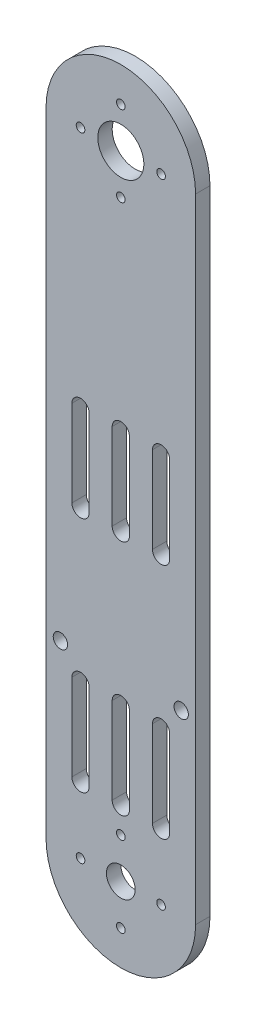
SolidWorks part; units mm, degrees
material "6061 合金"
ref_plane "前视基准面" through (0, 0, 0) normal (0, 0, 1) x (1, 0, 0)
ref_plane "上视基准面" through (0, 0, 0) normal (0, 1, 0) x (1, 0, 0)
ref_plane "右视基准面" through (0, 0, 0) normal (1, 0, 0) x (0, 0, -1)
other "质心 (COM)"
sketch "草图1" plane through (0, 0, 0) normal (0, 0, 1) x (1, 0, 0)
  line L0 (0, 23) -> (0, 53) construction
  line L4 (0, 23) -> (0, 53) construction
  line L23 (-3, 23) -> (-3, 53)
  line L87 (3, 23) -> (3, 53)
  line L88 (0, 23) -> (-14, 23) construction
  line L95 (-14, 23) -> (-14, 53) construction
  line L174 (-17, 23) -> (-17, 53)
  line L175 (-11, 23) -> (-11, 53)
  line L176 (0, 0) -> (0, 110) construction
  line L177 (-26, 220) -> (-26, 0)
  line L178 (-58.7183, 110) -> (53.7841, 110) construction
  line L179 (26, 220) -> (26, 0)
  line L180 (0, 220) -> (0, 161.5) construction
  line L181 (21, 62) -> (21, 110) construction
  line L182 (-21, 62) -> (-21, 110) construction
  line L183 (-19, 110) -> (-19, 131) construction
  line L184 (-31.1577, 62) -> (32.7845, 62) construction
  line L185 (2.4, 40.8) -> (18.4, 52.8) construction
  line L186 (20, 40) -> (20, 52) construction
  line L187 (3, 39) -> (19, 39) construction
  line L188 (3, 36) -> (19, 36) construction
  line L189 (2.4, 34.2) -> (18.4, 22.2) construction
  line L190 (20, 35) -> (20, 23) construction
  line L191 (-2.4, 34.2) -> (-18.4, 22.2) construction
  line L192 (-20, 35) -> (-20, 23) construction
  line L193 (-3, 36) -> (-19, 36) construction
  line L194 (-2.4, 40.8) -> (-18.4, 52.8) construction
  line L195 (-20, 40) -> (-20, 52) construction
  line L196 (-3, 39) -> (-19, 39) construction
  line L197 (20, 136) -> (20, 148) construction
  line L198 (2.4, 136.8) -> (18.4, 148.8) construction
  line L199 (-20, 136) -> (-20, 148) construction
  line L200 (20, 131) -> (20, 119) construction
  line L201 (-2.4, 136.8) -> (-18.4, 148.8) construction
  line L202 (3, 132) -> (19, 132) construction
  line L203 (2.4, 130.2) -> (18.4, 118.2) construction
  line L204 (-3, 135) -> (-19, 135) construction
  line L205 (-3, 132) -> (-19, 132) construction
  line L206 (-20, 131) -> (-20, 119) construction
  line L207 (-2.4, 130.2) -> (-18.4, 118.2) construction
  line L208 (3, 135) -> (19, 135) construction
  line L209 (14, 23) -> (14, 53) construction
  line L212 (17, 23) -> (17, 53)
  line L215 (0, 105.5) -> (0, 135.5) construction
  line L218 (-3, 105.5) -> (-3, 135.5)
  line L221 (11, 23) -> (11, 53)
  line L222 (0, 105.5) -> (0, 135.5) construction
  line L224 (3, 105.5) -> (3, 135.5)
  line L225 (0, 105.5) -> (-14, 105.5) construction
  line L226 (-14, 105.5) -> (-14, 135.5) construction
  line L227 (-17, 105.5) -> (-17, 135.5)
  line L228 (-11, 105.5) -> (-11, 135.5)
  line L229 (14, 105.5) -> (14, 135.5) construction
  line L230 (17, 105.5) -> (17, 135.5)
  line L231 (11, 105.5) -> (11, 135.5)
  arc A11 (-3, 23) -> (3, 23) centre (0, 23) ccw
  arc A187 (-26, 0) -> (26, 0) centre (0, 0) ccw
  circle A188 centre (0, 0) radius 5
  circle A189 centre (0, 0) radius 14 construction
  circle A190 centre (0, -14) radius 1.5
  circle A191 centre (0, 220) radius 22 construction
  circle A192 centre (0, 242) radius 2 construction
  circle A193 centre (0, 220) radius 8
  arc A194 (-26, 220) -> (26, 220) centre (0, 220) cw
  circle A195 centre (-14, 0) radius 1.5
  circle A196 centre (0, 14) radius 1.5
  circle A197 centre (14, 0) radius 1.5
  circle A198 centre (22, 220) radius 2 construction
  circle A199 centre (0, 198) radius 2 construction
  circle A200 centre (-22, 220) radius 2 construction
  circle A201 centre (-21, 62) radius 2.5
  circle A202 centre (21, 62) radius 2.5
  arc A203 (2.4, 40.8) -> (3, 39) centre (3, 40) ccw construction
  arc A204 (20, 52) -> (18.4, 52.8) centre (19, 52) ccw construction
  arc A205 (19, 39) -> (20, 40) centre (19, 40) ccw construction
  arc A206 (2.4, 34.2) -> (3, 36) centre (3, 35) cw construction
  arc A207 (20, 23) -> (18.4, 22.2) centre (19, 23) cw construction
  arc A208 (19, 36) -> (20, 35) centre (19, 35) cw construction
  arc A209 (-2.4, 34.2) -> (-3, 36) centre (-3, 35) ccw construction
  arc A210 (-20, 23) -> (-18.4, 22.2) centre (-19, 23) ccw construction
  arc A211 (-19, 36) -> (-20, 35) centre (-19, 35) ccw construction
  arc A212 (-20, 52) -> (-18.4, 52.8) centre (-19, 52) cw construction
  arc A213 (-19, 39) -> (-20, 40) centre (-19, 40) cw construction
  arc A214 (-2.4, 40.8) -> (-3, 39) centre (-3, 40) cw construction
  circle A215 centre (0, 161.5) radius 5.5 construction
  arc A216 (3, 53) -> (-3, 53) centre (0, 53) ccw
  circle A220 centre (0, 220) radius 14 construction
  circle A221 centre (0, 234) radius 1.5
  circle A222 centre (14, 220) radius 1.5
  circle A223 centre (0, 206) radius 1.5
  circle A224 centre (-14, 220) radius 1.5
  arc A225 (-17, 23) -> (-11, 23) centre (-14, 23) ccw
  arc A235 (-2.4, 136.8) -> (-3, 135) centre (-3, 136) cw construction
  arc A236 (-2.4, 130.2) -> (-3, 132) centre (-3, 131) ccw construction
  arc A237 (19, 135) -> (20, 136) centre (19, 136) ccw construction
  arc A238 (-20, 148) -> (-18.4, 148.8) centre (-19, 148) cw construction
  arc A239 (-20, 119) -> (-18.4, 118.2) centre (-19, 119) ccw construction
  arc A240 (2.4, 130.2) -> (3, 132) centre (3, 131) cw construction
  arc A241 (-19, 135) -> (-20, 136) centre (-19, 136) cw construction
  arc A242 (-19, 132) -> (-20, 131) centre (-19, 131) ccw construction
  arc A243 (20, 119) -> (18.4, 118.2) centre (19, 119) cw construction
  arc A244 (2.4, 136.8) -> (3, 135) centre (3, 136) ccw construction
  arc A245 (20, 148) -> (18.4, 148.8) centre (19, 148) ccw construction
  arc A246 (19, 132) -> (20, 131) centre (19, 131) cw construction
  arc A255 (-11, 53) -> (-17, 53) centre (-14, 53) ccw
  arc A256 (17, 23) -> (11, 23) centre (14, 23) cw
  arc A257 (11, 53) -> (17, 53) centre (14, 53) cw
  arc A258 (-3, 105.5) -> (3, 105.5) centre (0, 105.5) ccw
  arc A259 (3, 135.5) -> (-3, 135.5) centre (0, 135.5) ccw
  arc A260 (-17, 105.5) -> (-11, 105.5) centre (-14, 105.5) ccw
  arc A261 (-11, 135.5) -> (-17, 135.5) centre (-14, 135.5) ccw
  arc A262 (17, 105.5) -> (11, 105.5) centre (14, 105.5) cw
  arc A263 (11, 135.5) -> (17, 135.5) centre (14, 135.5) cw
  point P2 (0, 38)
  point P9 (-14, 38)
  point P17 (14, 38)
  point P27 (0, 120.5)
  point P35 (-14, 120.5)
  point P42 (14, 120.5)
  point P205 (0, 220)
  point P208 (0, 0)
  point P212 (0, 220)
  point P222 (0, 161.5)
  dimension "D14" = 110
  dimension "D3" = 14
  dimension "D4" = 14
  dimension "D15" = 26
  dimension "D16" = 48
  dimension "D17" = 5
  dimension "D18" = 48
  dimension "D19" = 5
  dimension "D21" = 58.5
extrude "凸台-拉伸1" add sketch "草图1" along normal blind 5
